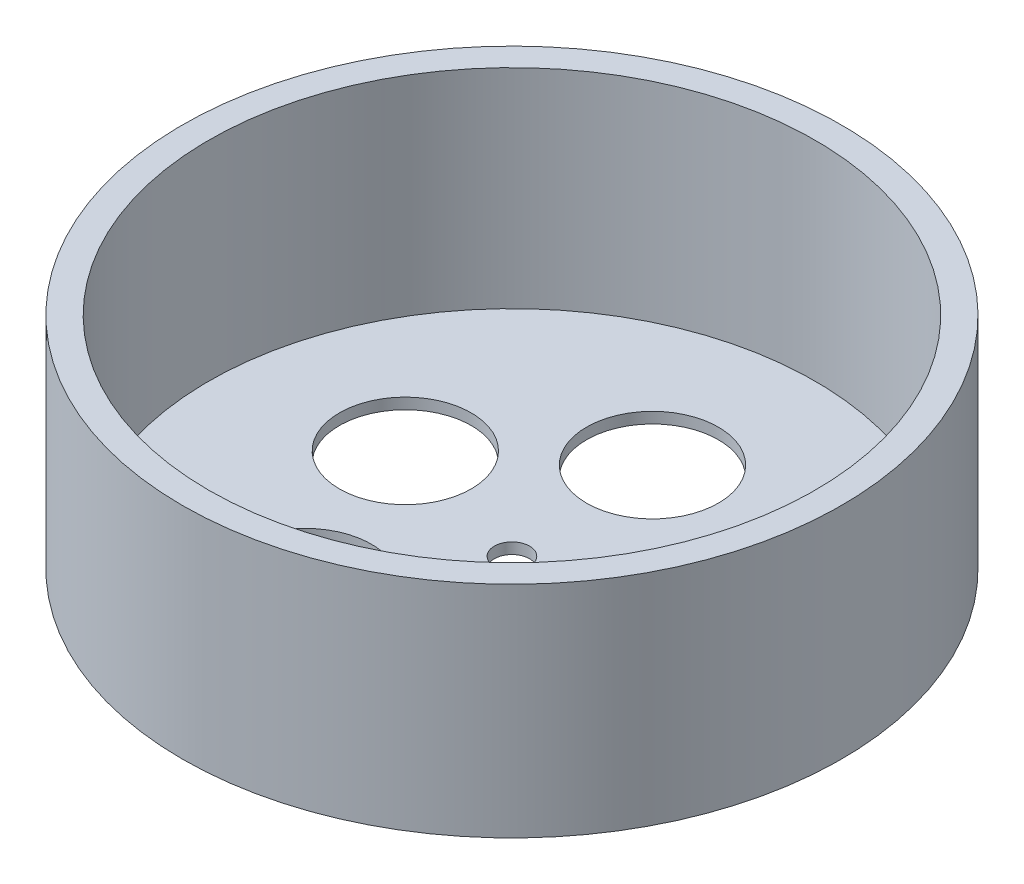
SolidWorks part; units mm, degrees
ref_plane "Front Plane" through (0, 0, 0) normal (0, 0, 1) x (1, 0, 0)
ref_plane "Top Plane" through (0, 0, 0) normal (0, 1, 0) x (1, 0, 0)
ref_plane "Right Plane" through (0, 0, 0) normal (1, 0, 0) x (0, 0, -1)
sketch "Sketch1" plane through (0, 0, 0) normal (0, 1, 0) x (1, 0, 0)
  circle A0 centre (0, 0) radius 150
extrude "Boss-Extrude1" add sketch "Sketch1" along normal blind 100
sketch "Sketch3" plane through (0, 100, 0) normal (0, 1, 0) x (1, 0, 0)
  circle A0 centre (0, 0) radius 138
extrude "Cut-Extrude1" cut sketch "Sketch3" against normal blind 95
sketch "Sketch4" plane through (0, 5, 0) normal (0, 1, 0) x (1, 0, 0)
  circle A1 centre (0, 0) radius 68 construction
  circle A2 centre (-3.92, 67.8869) radius 30
  circle A3 centre (63.353, 24.7063) radius 30
  circle A4 centre (43.0743, -52.6176) radius 30
  circle A5 centre (-36.7316, -57.2258) radius 30
  circle A6 centre (-65.7756, 17.2501) radius 30
  point P16 (0, 0)
  dimension "D1" = 5
extrude "Cut-Extrude2" cut sketch "Sketch4" against normal blind 8 contours A5 | A4 | A3 | A2 | A6
sketch "Sketch5" plane through (0, 5, 0) normal (0, 1, 0) x (1, 0, 0)
  circle A0 centre (0, 0) radius 8
extrude "Cut-Extrude3" cut sketch "Sketch5" against normal blind 8
scale "Scale1" scale about origin uniform scaling yes scale factor 0.01
